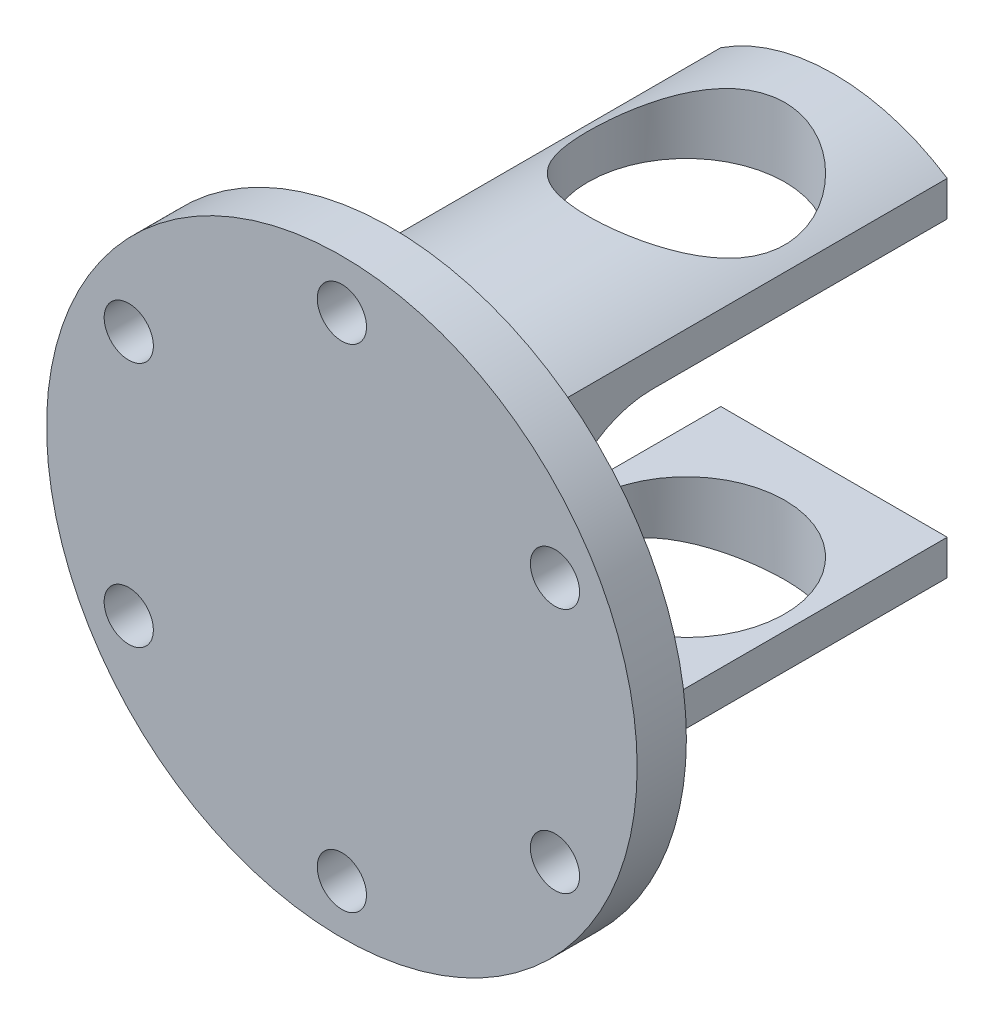
SolidWorks part; units mm, degrees
ref_plane "Płaszczyzna przednia" through (0, 0, 0) normal (0, 0, 1) x (1, 0, 0)
ref_plane "Płaszczyzna górna" through (0, 0, 0) normal (0, 1, 0) x (1, 0, 0)
ref_plane "Płaszczyzna prawa" through (0, 0, 0) normal (1, 0, 0) x (0, 0, -1)
sketch "Szkic1" plane through (0, 0, 0) normal (0, 0, 1) x (1, 0, 0)
  circle A1 centre (0, 0) radius 21
  dimension "D2" = 42
extrude "Dodanie-wyciągnięcie1" add sketch "Szkic1" along normal blind 5
sketch "Szkic2" plane through (0, 0, 0) normal (0, 0, -1) x (-1, 0, 0)
  line L0 (-11.5, 17.5713) -> (-11.5, 14)
  line L1 (-11.5, 14) -> (11.5, 14)
  line L2 (11.5, 14) -> (11.5, 17.5713)
  line L3 (0, 0) -> (-13.0295, 0) construction
  line L4 (11.5, -14) -> (11.5, -17.5713)
  line L5 (-11.5, -14) -> (11.5, -14)
  line L6 (-11.5, -17.5713) -> (-11.5, -14)
  circle A0 centre (0, 0) radius 21 construction
  arc A1 (-11.5, -17.5713) -> (11.5, -17.5713) centre (0, 0) ccw
  arc A2 (11.5, 17.5713) -> (-11.5, 17.5713) centre (0, 0) ccw
  dimension "D1" = 14
  dimension "D2" = 23
extrude "Dodanie-wyciągnięcie2" add sketch "Szkic2" along normal blind 40
sketch "Szkic4" plane through (0, -14, 0) normal (0, 1, 0) x (1, 0, 0)
  line L0 (11.5, 40) -> (-11.5, 40) construction
  circle A0 centre (0, 25) radius 10
  dimension "D1" = 20
  dimension "D2" = 15
extrude "Wytnij-wyciągnięcie1" cut sketch "Szkic4" against normal up to next and the other way through all
fillet "Zaokrąglenie1" radius 10 2 edges at (0, -14, 0) (0, 14, 0)
sketch "Szkic6" plane through (0, 0, 5) normal (0, 0, 1) x (1, 0, 0)
  circle A0 centre (0, 0) radius 30
  dimension "D1" = 60
extrude "Dodanie-wyciągnięcie3" add sketch "Szkic6" along normal blind 5
sketch "Szkic7" plane through (0, 0, 10) normal (0, 0, 1) x (1, 0, 0)
  circle A0 centre (0, 25) radius 2.5
  dimension "D1" = 5
  dimension "D2" = 25
extrude "Wytnij-wyciągnięcie2" cut sketch "Szkic7" against normal blind 5
pattern_circular "Szyk kołowy1" count 6 over 360 about axis through (0, 0, 0) along (0, 0, 1) of "Wytnij-wyciągnięcie2"
